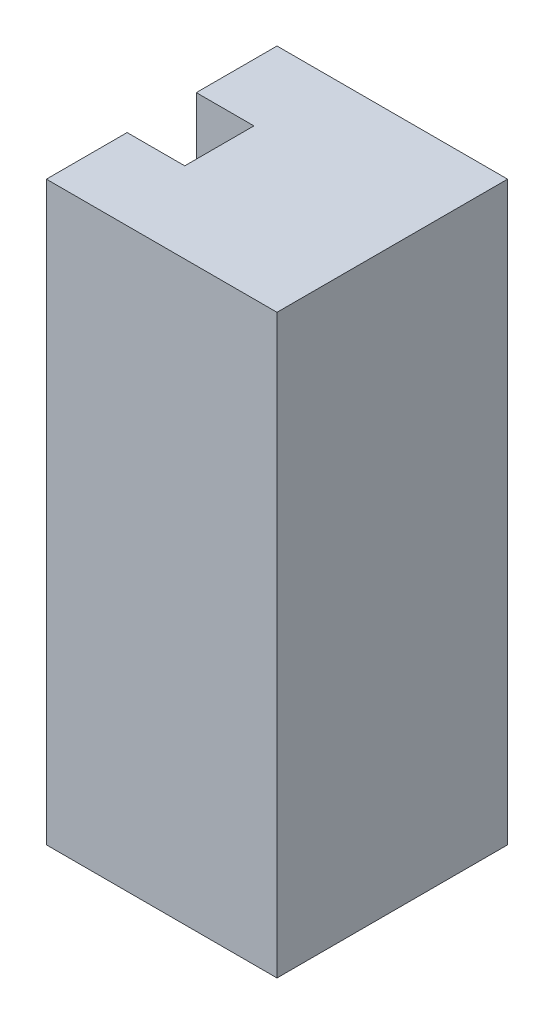
SolidWorks part; units mm, degrees
ref_plane "前视基准面" through (0, 0, 0) normal (0, 0, 1) x (1, 0, 0)
ref_plane "上视基准面" through (0, 0, 0) normal (0, 1, 0) x (1, 0, 0)
ref_plane "右视基准面" through (0, 0, 0) normal (1, 0, 0) x (0, 0, -1)
sketch "草图1" plane through (0, 0, 0) normal (0, 1, 0) x (1, 0, 0)
  line L1 (-8.7789, 3.8614) -> (11.2211, 3.8614)
  line L2 (-8.7789, 3.8614) -> (-8.7789, -16.1386)
  line L3 (-8.7789, -16.1386) -> (11.2211, -16.1386)
  line L4 (11.2211, 3.8614) -> (11.2211, -16.1386)
  line L5 (-8.7789, 3.8614) -> (11.2211, -16.1386) construction
  line L6 (-8.7789, -16.1386) -> (11.2211, 3.8614) construction
  point P4 (1.2211, -6.1386)
  dimension "D1" = 20
  dimension "D2" = 20
extrude "凸台-拉伸1" add sketch "草图1" along normal blind 50
sketch "草图2" plane through (-8.7789, 0, 0) normal (-1, 0, 0) x (0, 0, 1)
  line L0 (6.1386, 0) -> (6.1386, 50) construction
  line L1 (-3.8614, 0) -> (16.1386, 0) construction
  line L2 (-3.8614, 50) -> (16.1386, 50) construction
  line L4 (3.1386, 50) -> (9.1386, 50)
  line L5 (3.1386, 50) -> (3.1386, 0)
  line L6 (3.1386, 0) -> (9.1386, 0)
  line L7 (9.1386, 50) -> (9.1386, 0)
  line L8 (6.1386, 0) -> (6.1386, 50) construction
  line L9 (3.1386, 25) -> (9.1386, 25) construction
  point P6 (6.1386, 25)
  dimension "D1" = 6
extrude "切除-拉伸1" cut sketch "草图2" against normal blind 5
